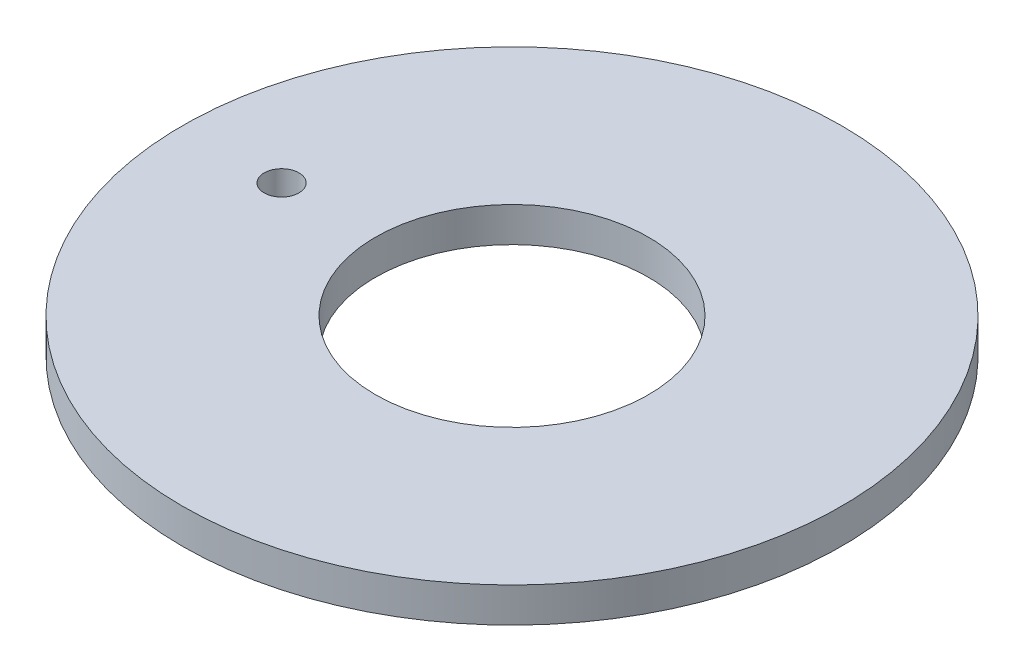
SolidWorks part; units mm, degrees
ref_plane "Front Plane" through (0, 0, 0) normal (0, 0, 1) x (1, 0, 0)
ref_plane "Top Plane" through (0, 0, 0) normal (0, 1, 0) x (1, 0, 0)
ref_plane "Right Plane" through (0, 0, 0) normal (1, 0, 0) x (0, 0, -1)
sketch "Sketch1" plane through (0, 0, 0) normal (0, 1, 0) x (1, 0, 0)
  circle A0 centre (0, 0) radius 37.9
  circle A1 centre (0, 0) radius 15.7
  dimension "D1" = 31.4
  dimension "D2" = 75.8
extrude "Boss-Extrude1" add sketch "Sketch1" along normal blind 4
sketch "Sketch2" plane through (0, 4, 0) normal (0, 1, 0) x (1, 0, 0)
  circle A0 centre (0, 0) radius 26.5 construction
  circle A1 centre (-26.5, 0) radius 2
  circle A2 centre (0, 0) radius 15.7 construction
  circle A3 centre (0, 0) radius 37.9 construction
  point P5 (-28.5, 0)
  point P6 (-24.5, 0)
  point P7 (-15.7, 0)
  point P8 (-37.9, 0)
  dimension "D1" = 53
  dimension "D2" = 4
extrude "Cut-Extrude1" cut sketch "Sketch2" against normal through all
